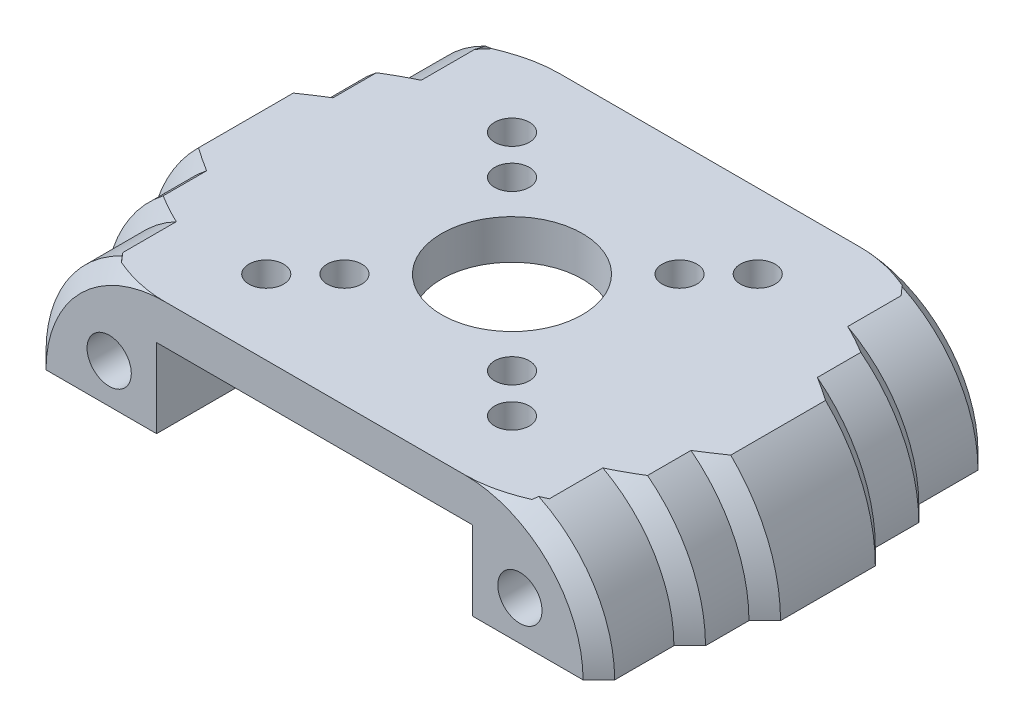
SolidWorks part; units mm, degrees
ref_plane "Front Plane" through (0, 0, 0) normal (0, 0, 1) x (1, 0, 0)
ref_plane "Top Plane" through (0, 0, 0) normal (0, 1, 0) x (1, 0, 0)
ref_plane "Right Plane" through (0, 0, 0) normal (1, 0, 0) x (0, 0, -1)
sketch "Sketch1" plane through (0, 0, 0) normal (0, 0, 1) x (1, 0, 0)
  line L2 (34, 6) -> (-34, 6)
  line L8 (-19, 21) -> (19, 21)
  line L9 (0, 6) -> (0, 0) construction
  arc A3 (34, 6) -> (19, 21) centre (19, 6) ccw
  arc A4 (-34, 6) -> (-19, 21) centre (-19, 6) cw
  point P0 (0, 0)
other "Pen Sketch3" parameters "D3"=16.8628, "D2"=15, "D1"=87.9869, "D4"=32.78, "D5"=10
extrude "Boss-Extrude1" add sketch "Sketch1" along normal blind 50 contours L8 A3 L2 A4
sketch "Sketch5" plane through (0, 6, 0) normal (0, -1, 0) x (1, 0, 0)
  line L0 (34, 0) -> (-34, 0) construction
  line L1 (-20, 0) -> (20, 0)
  line L2 (-20, 0) -> (-20, 50)
  line L3 (-20, 50) -> (20, 50)
  line L4 (20, 0) -> (20, 50)
  line L5 (34, 50) -> (-34, 50) construction
  point P8 (0, 0)
  point P9 (0, 0)
  point P11 (0, 0)
  dimension "D1" = 40
extrude "Cut-Extrude4" cut sketch "Sketch5" against normal blind 10
sketch "Sketch6" plane through (0, 21, 0) normal (0, 1, 0) x (1, 0, 0)
  line L0 (-19, 0) -> (19, 0) construction
  circle A0 centre (0, -25) radius 7.5
  dimension "D1" = 15
  dimension "D2" = 25
extrude "Cut-Extrude5" cut sketch "Sketch6" against normal blind 15
sketch "Sketch7" plane through (0, 0, 50) normal (0, 0, 1) x (1, 0, 0)
  line L0 (-26, 11) -> (-26, 6) construction
  line L1 (-20, 6) -> (-34, 6) construction
  line L2 (20, 16) -> (20, 6) construction
  line L3 (-26, 11) -> (-20, 11) construction
  line L4 (-20, 16) -> (-20, 6) construction
  line L5 (20, 11) -> (26, 11) construction
  line L6 (-23.2, 11) -> (-23.2, 7.6006) construction
  circle A0 centre (-26, 11) radius 2.8
  circle A1 centre (26, 11) radius 2.8
other "Pen Sketch2" parameters "D1"=6.4137, "D4"=4.3, "D2"=5.8357, "D3"=15
extrude "Cut-Extrude6" cut sketch "Sketch7" against normal through all both and the other way through all
sketch "Sketch8" plane through (0, 21, 0) normal (0, 1, 0) x (1, 0, 0)
  circle A0 centre (0, -25) radius 8.913
  circle A1 centre (0, -25) radius 15 construction
  circle A2 centre (0, -25) radius 22 construction
  circle A3 centre (0, -25) radius 31.5 construction
  circle A4 centre (10.6066, -14.3934) radius 2.2
  circle A5 centre (15.5563, -9.4437) radius 2.2
  circle A6 centre (-10.6066, -14.3934) radius 2.2
  circle A7 centre (-15.5563, -9.4437) radius 2.2
  circle A8 centre (-10.6066, -35.6066) radius 2.2
  circle A9 centre (-15.5563, -40.5563) radius 2.2
  circle A10 centre (10.6066, -35.6066) radius 2.2
  circle A11 centre (15.5563, -40.5563) radius 2.2
  point P0 (0, -25)
  point P22 (0, -25)
extrude "Cut-Extrude7" cut sketch "Sketch8" against normal blind 10
ref_plane "Plane1" through (0, 0, 25) normal (0, 0, 1) x (1, 0, 0)
sketch "Sketch9" plane through (0, 6, 0) normal (0, -1, 0) x (1, 0, 0)
  line L0 (34, 0) -> (36, 2)
  line L1 (36, 2) -> (36, 9.5)
  line L2 (36, 9.5) -> (38, 11.5)
  line L3 (38, 11.5) -> (38, 17)
  line L4 (38, 17) -> (40, 19)
  line L5 (40, 19) -> (40, 31)
  line L6 (40, 25) -> (34, 25) construction
  line L7 (34, 50) -> (34, 0) construction
  line L8 (34, 50) -> (34, 0)
  line L9 (34, 50) -> (36, 48)
  line L10 (36, 48) -> (36, 40.5)
  line L11 (36, 40.5) -> (38, 38.5)
  line L12 (38, 38.5) -> (38, 33)
  line L13 (38, 33) -> (40, 31)
  dimension "D1" = 135
  dimension "D2" = 2
  dimension "D3" = 135
  dimension "D4" = 2
  dimension "D5" = 2
  dimension "D6" = 7.5
  dimension "D7" = 5.5
sketch "Sketch11" plane through (0, 0, 0) normal (0, 0, -1) x (-1, 0, 0)
  line L0 (-19, 21) -> (19, 21)
  arc A0 (-19, 21) -> (-34, 6) centre (-19, 6) ccw
  arc A1 (19, 21) -> (34, 6) centre (19, 6) cw
sweep "Sweep2" add profiles "Sketch9" path "Sketch11"
sketch "Sketch12" plane through (0, 27, 0) normal (0, 1, 0) x (1, 0, 0)
  line L1 (-8.25, -25) -> (8.25, -25) construction
  circle A0 centre (0, -25) radius 35
  dimension "D1" = 70
extrude "Cut-Extrude8" cut sketch "Sketch12" against normal up to vertex (6 mm away)
